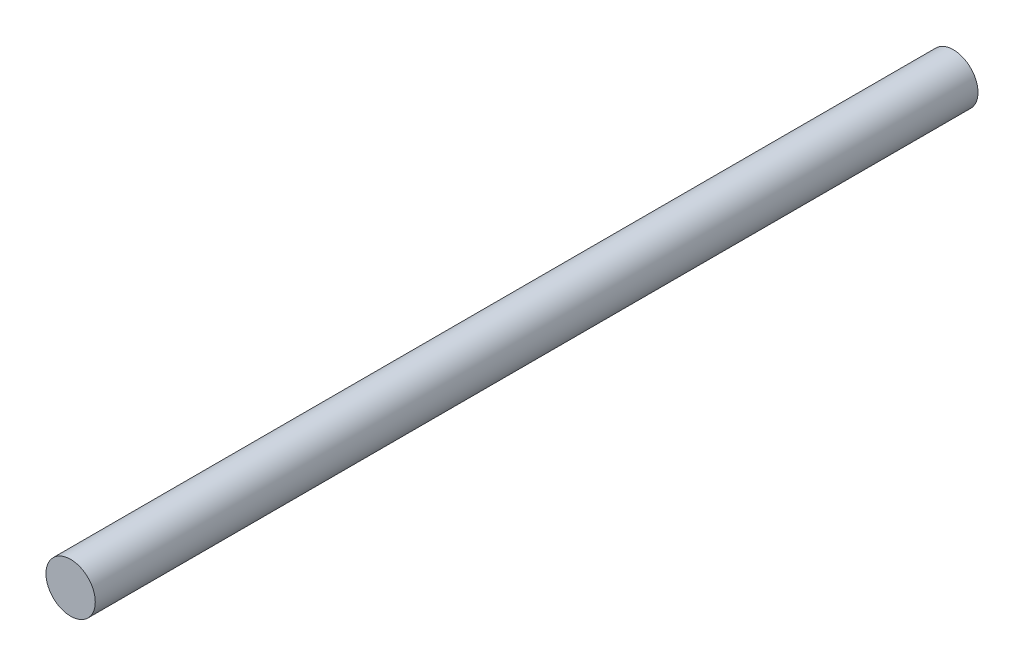
SolidWorks part; units mm, degrees
ref_plane "Front" through (0, 0, 0) normal (0, 0, 1) x (1, 0, 0)
ref_plane "Top" through (0, 0, 0) normal (0, 1, 0) x (1, 0, 0)
ref_plane "Right" through (0, 0, 0) normal (1, 0, 0) x (0, 0, -1)
sketch "Sketch1" plane through (0, 0, 0) normal (0, 0, 1) x (1, 0, 0)
  circle A0 centre (0, 0) radius 4.75
  dimension "D1" = 9.5
extrude "Boss-Extrude1" add sketch "Sketch1" along normal blind 170
equation "\"rod_length_zaxis\"=170"
equation "\"D1@Boss-Extrude1\"=\"rod_length_zaxis\""
